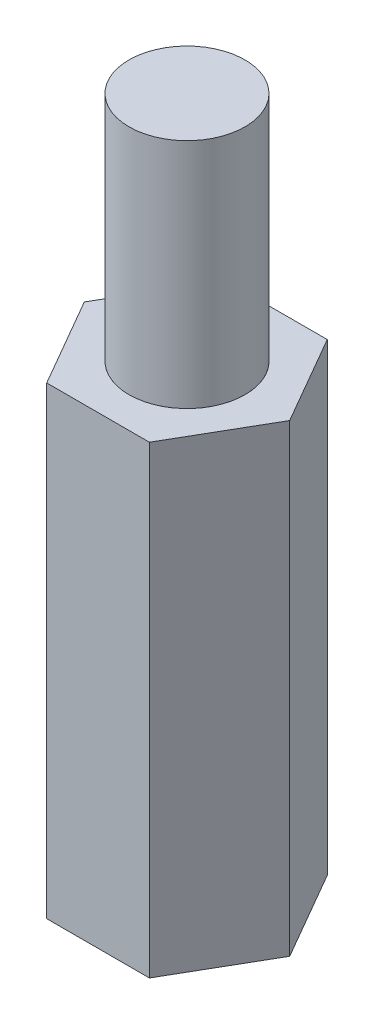
SolidWorks part; units mm, degrees
ref_plane "Front" through (0, 0, 0) normal (0, 0, 1) x (1, 0, 0)
ref_plane "Top" through (0, 0, 0) normal (0, 1, 0) x (1, 0, 0)
ref_plane "Right" through (0, 0, 0) normal (1, 0, 0) x (0, 0, -1)
sketch "草图1" plane through (0, 0, 0) normal (0, 1, 0) x (1, 0, 0)
  line L1 (-1.3279, 2.3) -> (-2.6558, 0)
  line L2 (-2.6558, 0) -> (-1.3279, -2.3)
  line L3 (-1.3279, -2.3) -> (1.3279, -2.3)
  line L4 (1.3279, -2.3) -> (2.6558, 0)
  line L5 (2.6558, 0) -> (1.3279, 2.3)
  line L6 (1.3279, 2.3) -> (-1.3279, 2.3)
  circle A0 centre (0, 0) radius 2.3 construction
  circle A1 centre (0, 0) radius 1.5 construction
  dimension "D2" = 3
  dimension "D1" = 4.6
extrude "凸台-拉伸1" add sketch "草图1" along normal blind 12
sketch "草图3" plane through (0, 12, 0) normal (0, 1, 0) x (1, 0, 0)
  circle A0 centre (0, 0) radius 1.5
  dimension "D1" = 3
extrude "凸台-拉伸2" add sketch "草图3" along normal blind 6
cosmetic thread "装饰螺纹线2" parameters "D2"=2
sketch "草图4" plane through (0, 0, 0) normal (0, -1, 0) x (1, 0, 0)
  circle A0 centre (0, 0) radius 1.5
  dimension "D1" = 3
extrude "切除-拉伸1" cut sketch "草图4" against normal up to surface (12 mm away) up to face at (0, 12, 1.5)
cosmetic thread "装饰螺纹线1"
ref_plane "基准面1" through (0, 6, 0) normal (0, 1, 0) x (1, 0, 0)
